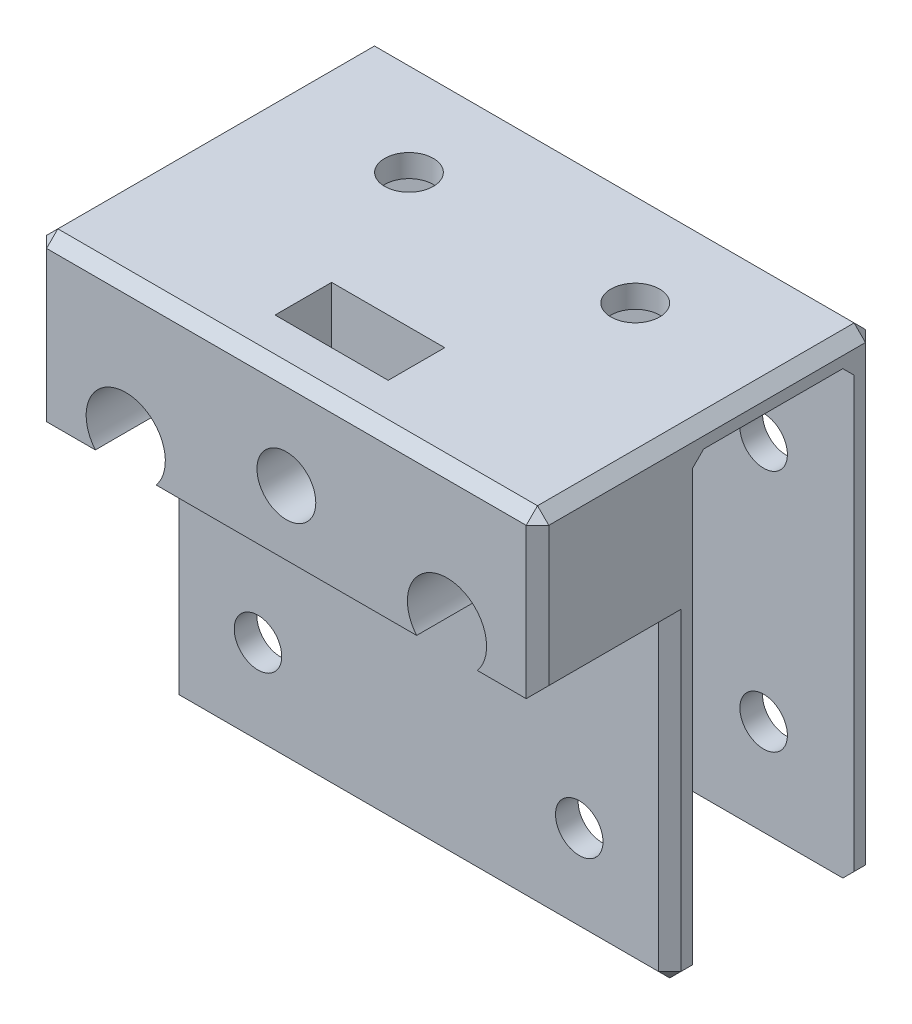
SolidWorks part; units mm, degrees
ref_plane "Front Plane" through (0, 0, 0) normal (0, 0, 1) x (1, 0, 0)
ref_plane "Top Plane" through (0, 0, 0) normal (0, 1, 0) x (1, 0, 0)
ref_plane "Right Plane" through (0, 0, 0) normal (1, 0, 0) x (0, 0, -1)
sketch "Sketch1" plane through (0, 0, 0) normal (0, 0, 1) x (1, 0, 0)
  line L0 (22.2, 40) -> (22.2, 0) construction
  line L1 (0, 0) -> (44.4, 0)
  line L2 (0, 0) -> (0, 40)
  line L3 (0, 40) -> (44.4, 40)
  line L4 (44.4, 0) -> (44.4, 40)
  line L5 (0, 0) -> (8, 0) construction
  line L6 (0, 0) -> (0, 8) construction
  line L10 (8, 29.9769) -> (8, 27.8769) construction
  line L11 (8, 19) -> (8, 8.4769) construction
  line L12 (8, 19) -> (10.573, 19) construction
  line L15 (10.573, 19) -> (10.573, 40) construction
  line L16 (8, 8.4769) -> (36.4, 8.4769) construction
  line L17 (36.4, 8.4769) -> (36.4, 29.9769) construction
  circle A0 centre (8, 8.4769) radius 2.1
  circle A1 centre (8, 29.9769) radius 2.1
  circle A2 centre (36.4, 29.9769) radius 2.1
  circle A3 centre (36.4, 8.4769) radius 2.1
  dimension "D5" = 4.2
  dimension "D6" = 4.2
  dimension "D7" = 4.2
  dimension "D8" = 4.2
  dimension "D1" = 44.4
  dimension "D2" = 40
  dimension "D3" = 21.5
  dimension "D4" = 21.5
  dimension "D9" = 21
  dimension "D10" = 8
  dimension "D11" = 8
extrude "Boss-Extrude1" add sketch "Sketch1" along normal blind 2
sketch "Sketch2" plane through (0, 40, 0) normal (0, 1, 0) x (1, 0, 0)
  line L0 (44.4, -2) -> (44.4, 0) construction
  line L1 (0, -2) -> (44.4, -2)
  line L2 (0, -2) -> (0, 16.3)
  line L3 (0, 16.3) -> (44.4, 16.3)
  line L4 (44.4, -2) -> (44.4, 16.3)
  dimension "D1" = 18.3
  dimension "D2" = 44.4
extrude "Boss-Extrude2" add sketch "Sketch2" along normal blind 2
pattern_linear "LPattern1" count 2 spacing 16.3 along (0, 0, -1) of "Boss-Extrude1"
sketch "Sketch3" plane through (0, 42, 0) normal (0, 1, 0) x (1, 0, 0)
  line L0 (22.2, 16.3) -> (22.2, -2) construction
  line L1 (44.4, 16.3) -> (0, 16.3) construction
  line L2 (0, -2) -> (44.4, -2) construction
  line L3 (22.2, 7.15) -> (12.2, 7.15) construction
  line L4 (22.2, 7.15) -> (32.2, 7.15) construction
  circle A0 centre (12.2, 7.15) radius 2.15
  circle A1 centre (32.2, 7.15) radius 2.15
  dimension "D3" = 4.3
  dimension "D4" = 4.3
  dimension "D1" = 10
  dimension "D2" = 10
extrude "Cut-Extrude1" cut sketch "Sketch3" against normal through all
sketch "Sketch5" plane through (0, 0, -16.3) normal (0, 0, -1) x (-1, 0, 0)
  line L1 (-22.2, 41) -> (-22.2, 34.93) construction
  dimension "D1" = 6.07
ref_plane "Plane1" through (22.2, 0, 0) normal (1, 0, 0) x (0, 0, -1)
sketch "Sketch6" plane through (22.2, 0, 0) normal (1, 0, 0) x (0, 0, -1)
  line L0 (16.3, 42) -> (-2, 42) construction
  line L1 (16.3, 41) -> (16.3, 34.93) construction
  line L3 (-2, 42) -> (-13.69, 42)
  line L4 (-13.69, 42) -> (-13.69, 27.73)
  line L5 (-13.69, 27.73) -> (-2, 27.73)
  line L6 (-2, 27.73) -> (-2, 42)
  dimension "D1" = 11.69
  dimension "D2" = 14.27
extrude "Boss-Extrude3" add sketch "Sketch6" along normal up to surface and the other way up to surface
sketch "Sketch7" plane through (0, 0, 13.69) normal (0, 0, 1) x (1, 0, 0)
  circle A0 centre (22.2, 33.43) radius 2.6
  dimension "D2" = 5.2
extrude "Cut-Extrude2" cut sketch "Sketch7" against normal up to next
sketch "Sketch8" plane through (0, 0, 0) normal (0, 0, -1) x (-1, 0, 0)
  circle A0 centre (-36.4, 29.9769) radius 2.1
  circle A1 centre (-8, 29.9769) radius 2.1
extrude "Cut-Extrude3" cut sketch "Sketch8" against normal up to next
sketch "Sketch9" plane through (0, 0, 13.69) normal (0, 0, 1) x (1, 0, 0)
  circle A0 centre (8, 29.9769) radius 3.5
  circle A1 centre (36.4, 29.9769) radius 3.5
  dimension "D1" = 7
  dimension "D2" = 7
extrude "Cut-Extrude4" cut sketch "Sketch9" against normal up to surface (11.69 mm away) up to face at (22.2, 13.865, 2)
fillet "Fillet4" radius 1 20 edges at (22.2, 40, -14.3) (22.2, 40, 0) (22.2, 42, -16.3) (0, 42, -1.305) (44.4, 42, -1.305) (44.4, 13.865, 2) (44.4, 21, -16.3) (0, 21, -16.3) (0, 13.865, 2) (44.4, 0, 1) (0, 0, 1) (44.4, 0, -15.3) (0, 0, -15.3) (22.2, 0, -16.3) (22.2, 0, 2) (22.2, 42, 13.69) (44.4, 27.73, 7.845) (0, 27.73, 7.845) (44.4, 34.865, 13.69) (0, 34.865, 13.69) profile chamfer
sketch "Sketch11" plane through (0, 42, 0) normal (0, 1, 0) x (1, 0, 0)
  line L1 (17.2, -9.69) -> (27.2, -9.69)
  line L2 (17.2, -9.69) -> (17.2, -4.69)
  line L3 (17.2, -4.69) -> (27.2, -4.69)
  line L4 (27.2, -9.69) -> (27.2, -4.69)
extrude "Cut-Extrude6" cut sketch "Sketch11" against normal offset from surface (12.27 mm away) 2 up to face at (22.2, 27.73, 7.845)
